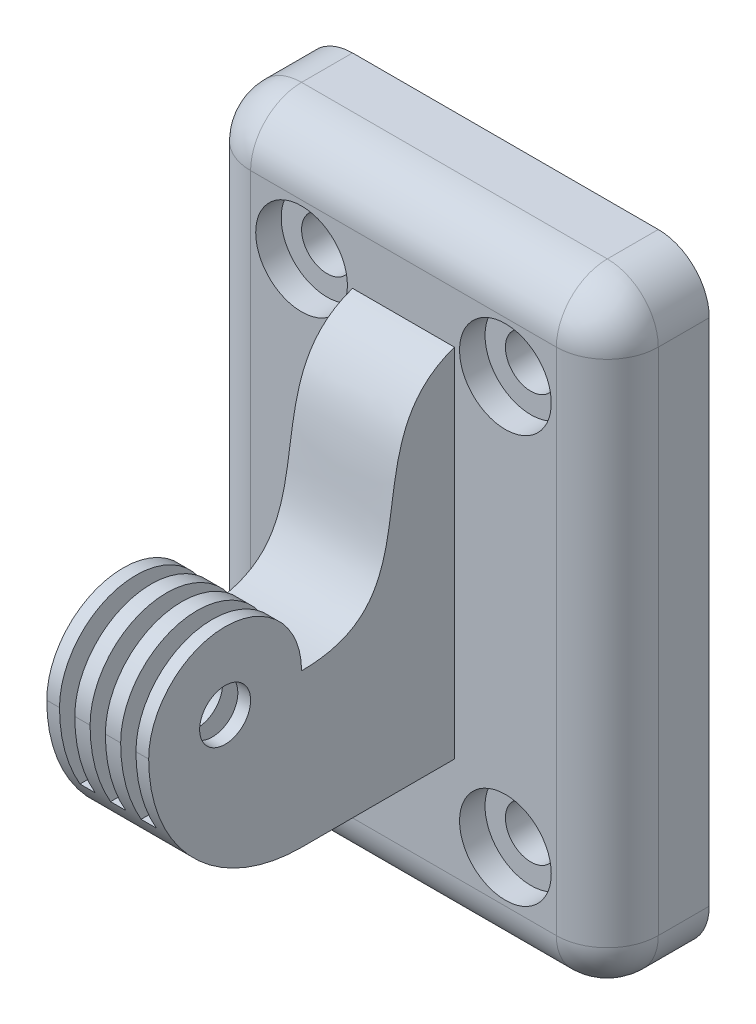
SolidWorks part; units mm, degrees
ref_plane "Front Plane" through (0, 0, 0) normal (0, 0, 1) x (1, 0, 0)
ref_plane "Top Plane" through (0, 0, 0) normal (0, 1, 0) x (1, 0, 0)
ref_plane "Right Plane" through (0, 0, 0) normal (1, 0, 0) x (0, 0, -1)
sketch "Sketch1" plane through (0, 0, 0) normal (0, 0, 1) x (1, 0, 0)
  line L1 (-20, -30) -> (20, -30)
  line L2 (-20, -30) -> (-20, 30)
  line L3 (-20, 30) -> (20, 30)
  line L4 (20, -30) -> (20, 30)
  line L5 (-20, -30) -> (20, 30) construction
  line L6 (-20, 30) -> (20, -30) construction
  point P0 (0, 0)
  dimension "D1" = 40
  dimension "D2" = 60
extrude "Boss-Extrude1" add sketch "Sketch1" along normal blind 10
sketch "Sketch2" plane through (0, 0, 10) normal (0, 0, 1) x (1, 0, 0)
  line L0 (0, 20) -> (0, -20) construction
  line L1 (-10, -20) -> (10, -20) construction
  line L2 (-10, -20) -> (-10, 20) construction
  line L3 (-10, 20) -> (10, 20) construction
  line L4 (10, -20) -> (10, 20) construction
  line L5 (-10, -20) -> (10, 20) construction
  line L6 (-10, 20) -> (10, -20) construction
  line L7 (-10, 0) -> (10, 0) construction
  circle A0 centre (-10, -20) radius 2.5
  circle A1 centre (10, -20) radius 2.5
  circle A2 centre (10, 20) radius 2.5
  circle A3 centre (-10, 20) radius 2.5
  point P0 (0, 0)
  dimension "D1" = 5
  dimension "D2" = 40
  dimension "D3" = 20
extrude "Cut-Extrude1" cut sketch "Sketch2" against normal blind 10
fillet "Fillet1" radius 5 4 edges at (20, 30, 5) (20, -30, 5) (-20, -30, 5) (-20, 30, 5)
fillet "Fillet2" radius 5 8 edges at (18.5355, -28.5355, 10) (0, -30, 10) (-18.5355, -28.5355, 10) (-20, 0, 10) (-18.5355, 28.5355, 10) (0, 30, 10) (18.5355, 28.5355, 10) (20, 0, 10)
sketch "Sketch3" plane through (0, 0, 0) normal (1, 0, 0) x (0, 0, -1)
  line L0 (-10, -15) -> (-25, -15)
  line L1 (-10, -25) -> (-10, 25) construction
  line L2 (-25, -15) -> (-25, 0) construction
  line L3 (-40, 0) -> (-32.5, 0) construction
  line L4 (-25, 0) -> (0, 0) construction
  line L5 (0, -25) -> (0, 25) construction
  line L6 (-10, -25) -> (-10, 25) construction
  line L7 (-10, 20) -> (-10, -15)
  arc A0 (-40, 0) -> (-25, -15) centre (-25, 0) ccw
  arc A1 (-25, 0) -> (-40, 0) centre (-32.5, 0) ccw
  spline S0 degree 3 poles (-25, 0) (-11.2065, 0.0234) (-20.5924, 16.3304) (-10, 20) knots 0 0 0 0 1 1 1 1
  point P4 (-11, 15)
  dimension "D2" = 4
  dimension "D1" = 15
  dimension "D4" = 15
  dimension "D5" = 20
  dimension "D6" = 15
  dimension "D7" = 17.5
  dimension "D8" = 25
extrude "Boss-Extrude2" add sketch "Sketch3" along normal mid plane 10
sketch "Sketch4" plane through (0, 0, 0) normal (1, 0, 0) x (0, 0, -1)
  line L0 (-32.5, -7.5) -> (-40, -7.5)
  line L1 (-40, -7.5) -> (-40, 0)
  arc A0 (-25, 0) -> (-40, 0) centre (-32.5, 0) ccw construction
  arc A1 (-25, 0) -> (-40, 0) centre (-32.5, 0) ccw construction
  arc A2 (-32.5, -7.5) -> (-40, 0) centre (-32.5, 0) ccw
extrude "Cut-Extrude2" cut sketch "Sketch4" against normal mid plane 1.5
pattern_linear "LPattern1" count 2 spacing 3 along (-1, 0, 0) of "Cut-Extrude2"
pattern_linear "LPattern2" count 2 spacing 3 along (1, 0, 0) of "Cut-Extrude2"
sketch "Sketch5" plane through (0, 0, 10) normal (0, 0, 1) x (1, 0, 0)
  line L0 (0, 30) -> (0, -30) construction
  line L1 (-15, 30) -> (15, 30) construction
  line L2 (15, -30) -> (-15, -30) construction
  line L3 (-20, 0) -> (20, 0) construction
  line L4 (-20, -25) -> (-20, 25) construction
  line L5 (20, 25) -> (20, -25) construction
  circle A1 centre (-10, -20) radius 4.5
  circle A2 centre (-10, 20) radius 4.5
  circle A3 centre (-10, 20) radius 4.5
  circle A4 centre (10, -20) radius 4.5
  circle A5 centre (10, 20) radius 4.5
  dimension "D1" = 2
extrude "Cut-Extrude3" cut sketch "Sketch5" against normal mid plane 5
sketch "Sketch6" plane through (5, 0, 0) normal (1, 0, 0) x (0, 0, -1)
  line L0 (-25, 0) -> (-40, 0) construction
  arc A0 (-25, 0) -> (-40, 0) centre (-32.5, 0) ccw construction
  circle A1 centre (-32.5, 0) radius 2.5
  dimension "D1" = 5
extrude "Cut-Extrude4" cut sketch "Sketch6" against normal mid plane 47
